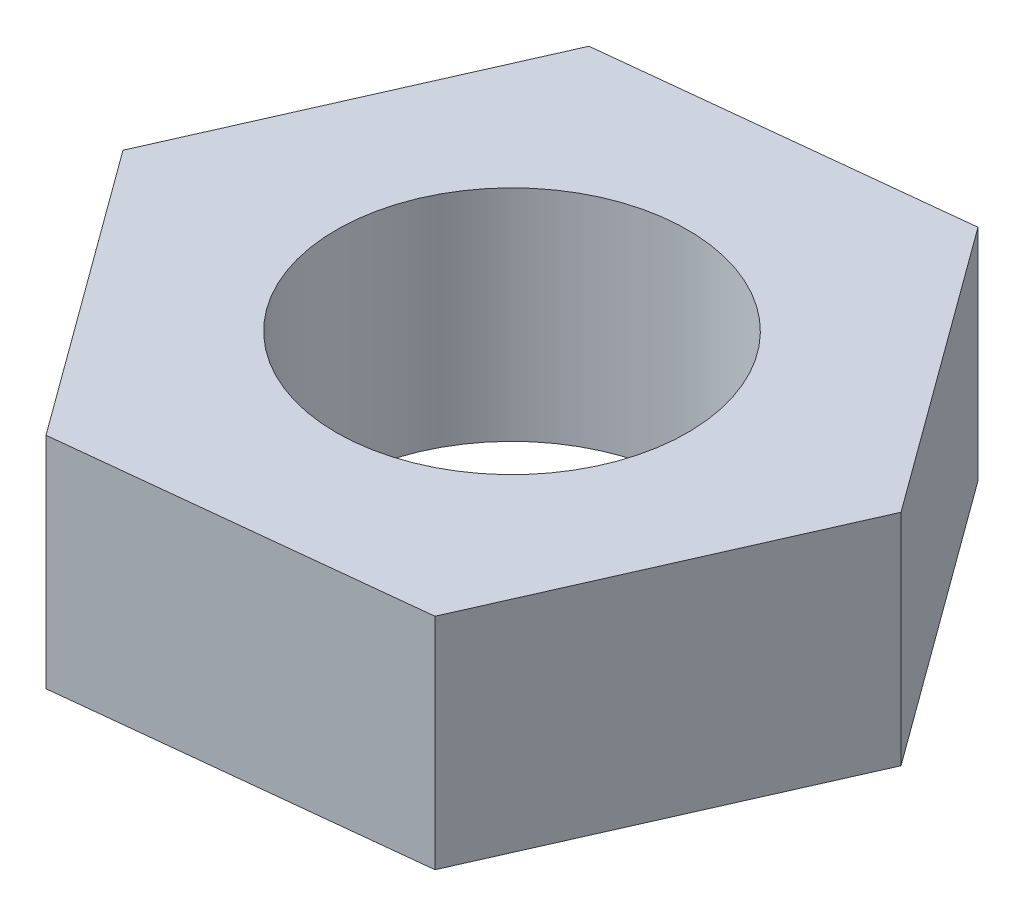
SolidWorks part; units mm, degrees
ref_plane "Front Plane" through (0, 0, 0) normal (0, 0, 1) x (1, 0, 0)
ref_plane "Top Plane" through (0, 0, 0) normal (0, 1, 0) x (1, 0, 0)
ref_plane "Right Plane" through (0, 0, 0) normal (1, 0, 0) x (0, 0, -1)
sketch "Sketch1" plane through (0, 0, 0) normal (0, 1, 0) x (1, 0, 0)
  line L1 (4.7444, -6.4976) -> (7.9993, 0.86)
  line L2 (7.9993, 0.86) -> (3.2549, 7.3576)
  line L3 (3.2549, 7.3576) -> (-4.7444, 6.4976)
  line L4 (-4.7444, 6.4976) -> (-7.9993, -0.86)
  line L5 (-7.9993, -0.86) -> (-3.2549, -7.3576)
  line L6 (-3.2549, -7.3576) -> (4.7444, -6.4976)
  circle A0 centre (0, 0) radius 4
  circle A1 centre (0, 0) radius 6.9675 construction
extrude "Boss-Extrude1" add sketch "Sketch1" along normal blind 5
